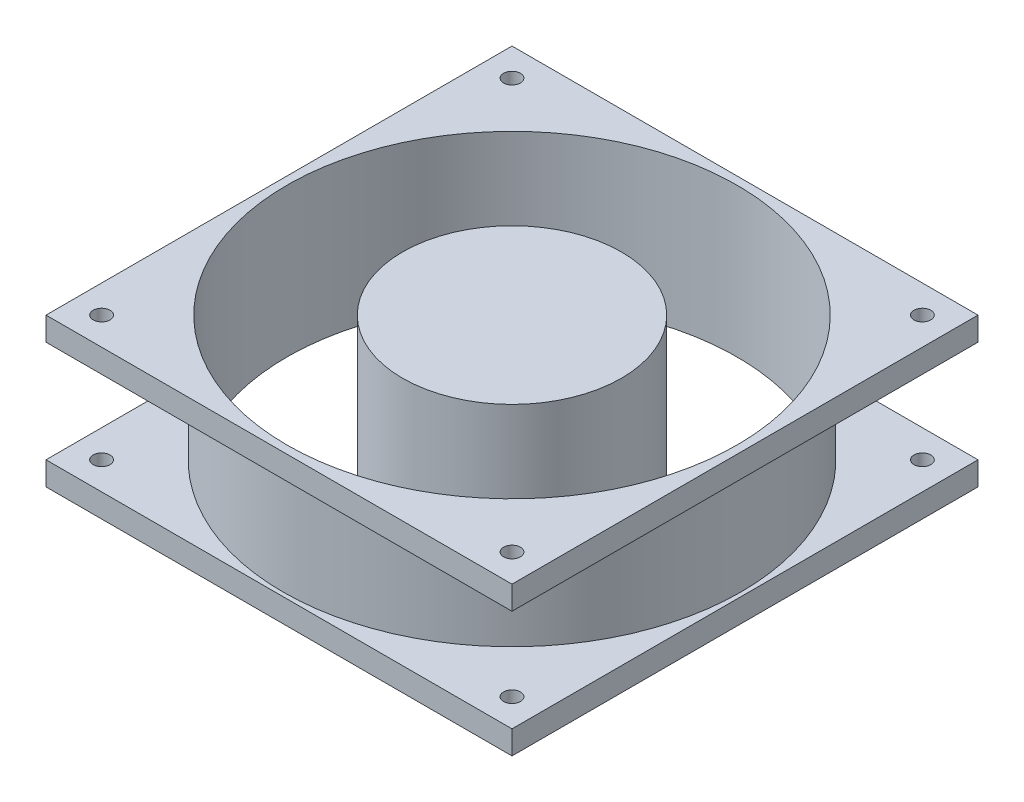
SolidWorks part; units mm, degrees
ref_plane "Front Plane" through (0, 0, 0) normal (0, 0, 1) x (1, 0, 0)
ref_plane "Top Plane" through (0, 0, 0) normal (0, 1, 0) x (1, 0, 0)
ref_plane "Right Plane" through (0, 0, 0) normal (1, 0, 0) x (0, 0, -1)
sketch "Sketch1" plane through (0, 0, 0) normal (0, 1, 0) x (1, 0, 0)
  line L1 (-59.5, 59.5) -> (59.5, 59.5)
  line L2 (-59.5, 59.5) -> (-59.5, -59.5)
  line L3 (-59.5, -59.5) -> (59.5, -59.5)
  line L4 (59.5, 59.5) -> (59.5, -59.5)
  line L11 (52.4, -52.4) -> (-52.4, -52.4) construction
  line L12 (52.4, -52.4) -> (52.4, 52.4) construction
  line L13 (52.4, 52.4) -> (-52.4, 52.4) construction
  line L14 (-52.4, -52.4) -> (-52.4, 52.4) construction
  line L15 (52.4, -52.4) -> (-52.4, 52.4) construction
  line L16 (52.4, 52.4) -> (-52.4, -52.4) construction
  circle A0 centre (0, 0) radius 57.468
  circle A1 centre (0, 0) radius 59.5 construction
  circle A4 centre (-52.4, 52.4) radius 2.15
  circle A6 centre (52.4, 52.4) radius 2.15
  circle A7 centre (52.4, -52.4) radius 2.15
  circle A8 centre (-52.4, -52.4) radius 2.15
  point P4 (-59.5, 0)
  point P18 (0, 59.5)
  dimension "D1" = 2.032
  dimension "D4" = 4.3
  dimension "D2" = 119
  dimension "D5" = 104.8
extrude "Boss-Extrude1" add sketch "Sketch1" along normal blind 6 from offset 19
sketch "Sketch2" plane through (0, -13, 0) normal (0, 1, 0) x (-1, 0, 0)
  circle A0 centre (0, 0) radius 57.468
  circle A1 centre (0, 0) radius 58.484
  circle A3 centre (0, 0) radius 57.468 construction
  dimension "D1" = 1.016
extrude "Boss-Extrude2" add sketch "Sketch2" along normal blind 26.2 from offset 0.1 offset against normal yes
mirror "Mirror5" about plane through (0, 0, 0) normal (0, 1, 0) of "Boss-Extrude1"
sketch "Sketch3" plane through (0, 0, 0) normal (0, 1, 0) x (1, 0, 0)
  circle A0 centre (0, 0) radius 27.94
  dimension "D1" = 55.88
extrude "Boss-Extrude3" add sketch "Sketch3" along normal mid plane 38 separate body
